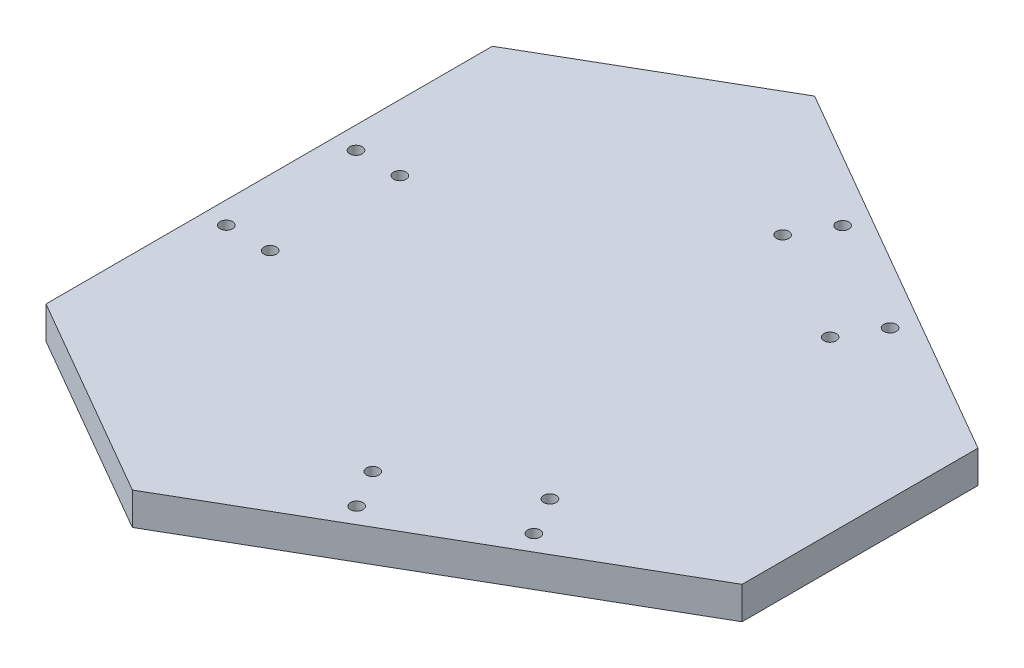
SolidWorks part; units mm, degrees
material "1060 Alloy"
ref_plane "Front Plane" through (0, 0, 0) normal (0, 0, 1) x (1, 0, 0)
ref_plane "Top Plane" through (0, 0, 0) normal (0, 1, 0) x (1, 0, 0)
ref_plane "Right Plane" through (0, 0, 0) normal (1, 0, 0) x (0, 0, -1)
sketch "Sketch2" plane through (0, 0, 0) normal (0, 1, 0) x (1, 0, 0)
  line L0 (-103.792, 179.773) -> (-103.792, -179.773) construction
  line L1 (173.2051, 0) -> (-86.6025, 150) construction
  line L2 (-86.6025, 150) -> (-86.6025, -150) construction
  line L3 (-86.6025, -150) -> (173.2051, 0) construction
  line L4 (0, 0) -> (43.3013, -75) construction
  line L5 (0, 0) -> (43.3013, 75) construction
  line L6 (0, 0) -> (-86.6025, 0) construction
  line L7 (-103.792, -179.773) -> (207.584, 0) construction
  line L8 (207.584, 0) -> (-103.792, 179.773) construction
  line L15 (127.584, 46.188) -> (127.584, -46.188)
  line L16 (-23.792, 133.585) -> (-103.792, 87.397)
  line L17 (-103.792, -87.397) -> (-23.792, -133.585)
  line L18 (-103.792, 87.397) -> (-103.792, -87.397)
  line L19 (-23.792, -133.585) -> (127.584, -46.188)
  line L20 (-23.792, 133.585) -> (127.584, 46.188)
  line L21 (-9.282, -85.5203) -> (7.8923, -115.2727) construction
  line L22 (-9.282, -85.5203) -> (78.7102, -34.7273) construction
  line L23 (7.8923, -115.2727) -> (95.8846, -64.4797) construction
  line L24 (78.7102, -34.7273) -> (95.8846, -64.4797) construction
  line L25 (-9.282, -85.5203) -> (95.8846, -64.4797) construction
  line L26 (7.8923, -115.2727) -> (78.7102, -34.7273) construction
  line L27 (43.3013, -75) -> (51.896, -89.8865) construction
  line L28 (47.5986, -82.4433) -> (91.5942, -57.0471) construction
  circle A0 centre (0, 0) radius 86.6025 construction
  circle A1 centre (69.5964, -69.7452) radius 2.4511
  circle A2 centre (25.6029, -95.1448) radius 2.4511
  circle A3 centre (60.9996, -54.8552) radius 2.4511
  circle A4 centre (17.0061, -80.2548) radius 2.4511
  circle A5 centre (-78.0058, -25.3997) radius 2.4511
  circle A6 centre (-95.1993, -25.3997) radius 2.4511
  circle A7 centre (-95.1993, 25.3997) radius 2.4511
  circle A8 centre (-78.0058, 25.3997) radius 2.4511
  circle A9 centre (60.9996, 54.8552) radius 2.4511
  circle A10 centre (69.5964, 69.7452) radius 2.4511
  circle A11 centre (25.6029, 95.1448) radius 2.4511
  circle A12 centre (17.0061, 80.2548) radius 2.4511
  point P8 (60.6218, -65)
  point P12 (25.9808, -85)
  point P14 (-86.6025, 20)
  point P17 (-86.6025, -20)
  point P20 (60.6218, 65)
  point P21 (25.9808, 85)
  dimension "D7" = 4.9022
  dimension "D1" = 300
  dimension "D2" = 17.1894
  dimension "D3" = 130
  dimension "D4" = 80
  dimension "D5" = 101.6
  dimension "D6" = 34.3535
extrude "Boss-Extrude1" add sketch "Sketch2" along normal blind 12.7
